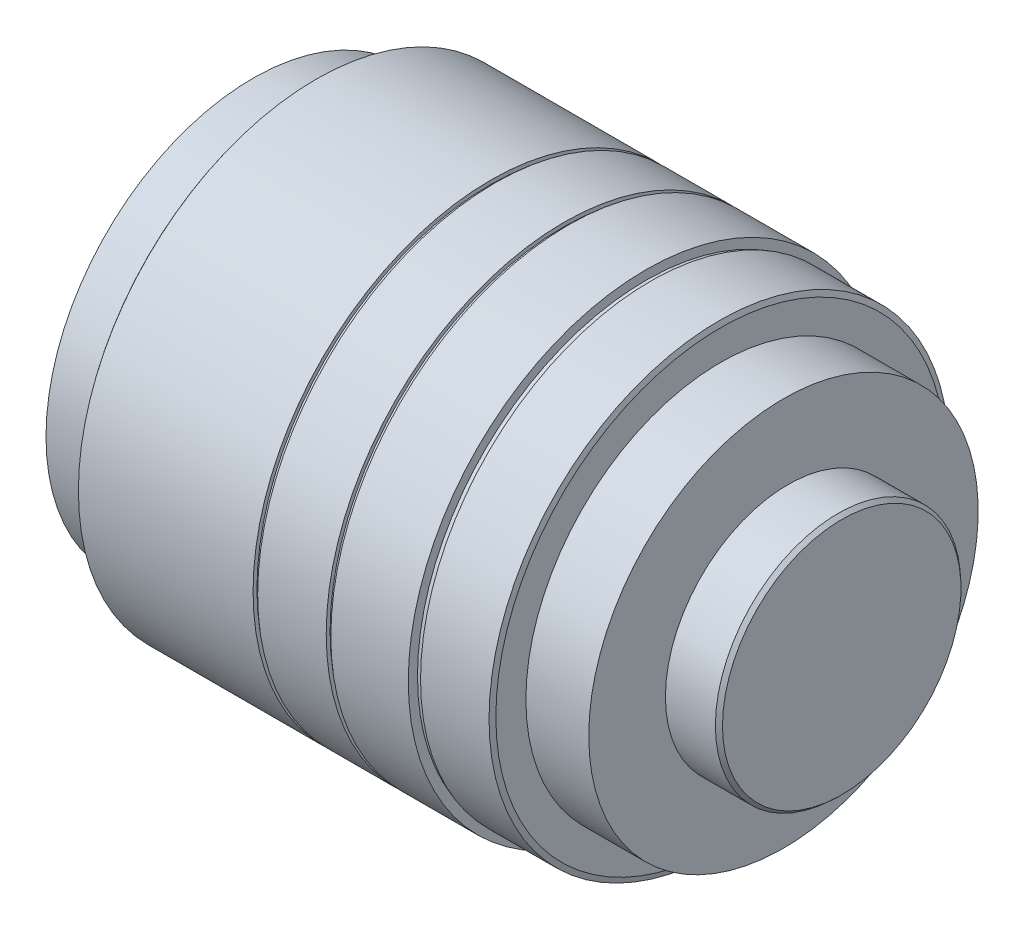
SolidWorks part; units mm, degrees
ref_plane "Front Plane" through (0, 0, 0) normal (0, 0, 1) x (1, 0, 0)
ref_plane "Top Plane" through (0, 0, 0) normal (0, 1, 0) x (1, 0, 0)
ref_plane "Right Plane" through (0, 0, 0) normal (1, 0, 0) x (0, 0, -1)
sketch "Sketch1" plane through (0, 0, 0) normal (0, 0, 1) x (1, 0, 0)
  line L0 (-61.5959, 0) -> (17.8345, 0) construction
  line L1 (-38.4, 0) -> (-38.4, 13.5)
  line L2 (-38.4, 13.5) -> (-34.4, 13.5)
  line L3 (-34.4, 13.5) -> (-34.4, 15.3546)
  line L4 (-34.4, 15.3546) -> (-34.2875, 15.5)
  line L5 (-34.2875, 15.5) -> (-22.895, 15.5)
  line L6 (-22.895, 15.5) -> (-22.895, 15.2469)
  line L7 (-22.895, 15.2469) -> (-22.595, 15.2469)
  line L8 (-22.595, 15.2469) -> (-22.595, 15.5)
  line L9 (-22.595, 15.5) -> (-18.1236, 15.5)
  line L10 (-18.1236, 15.5) -> (-18.1236, 15.2469)
  line L11 (-18.1236, 15.2469) -> (-17.8236, 15.2469)
  line L12 (-17.8236, 15.2469) -> (-17.8236, 15.5)
  line L13 (-17.8236, 15.5) -> (-12.7715, 15.5)
  line L14 (-12.7715, 15.5) -> (-12.7715, 14.8998)
  line L15 (-12.7715, 14.8998) -> (-12.4715, 14.8998)
  line L16 (-12.4715, 14.8998) -> (-12.4715, 15)
  line L17 (-12.4715, 15) -> (-8.0041, 15)
  line L18 (-8.0041, 15) -> (-7.9, 14.6603)
  line L19 (-7.9, 14.6603) -> (-7.9, 12.7)
  line L20 (-7.9, 12.7) -> (-3.7998, 12.7)
  line L21 (-3.7998, 12.7) -> (-3.7998, 7.5151)
  line L22 (-3.7998, 7.5151) -> (-3.4998, 7.5151)
  line L23 (-3.4998, 7.5151) -> (-3.4998, 8)
  line L24 (-3.4998, 8) -> (-0.2409, 8)
  line L25 (-0.2409, 8) -> (0, 7.7775)
  line L26 (0, 7.7775) -> (0, 0)
  line L27 (-38.4, 0) -> (0, 0)
  dimension "D1" = 16
  dimension "D2" = 7.9
  dimension "D3" = 30.5
  dimension "D4" = 31
  dimension "D5" = 27
  dimension "D6" = 30
  dimension "D7" = 26.5
  dimension "D8" = 0.3
  dimension "D9" = 0.3
  dimension "D10" = 0.3
  dimension "D11" = 25.4
  dimension "D12" = 0.3
revolve "Revolve1" add sketch "Sketch1" angle 360 about L0
sketch "Sketch2" plane through (0, 0, 0) normal (0, 1, 0) x (1, 0, 0)
  line L0 (-49.3696, 0) -> (5.4729, 0) construction
  line L2 (-38.4, 13.5) -> (-38.4, -13.5) construction
  line L3 (-38.4, -9.1129) -> (-38.4, 0)
  line L4 (-38.4, 0) -> (-40.6113, 0)
  arc A0 (-38.4, -9.1129) -> (-40.6113, 0) centre (-23.0366, -0.5601) cw
revolve "Revolve2" add sketch "Sketch2" angle 360 about L0
